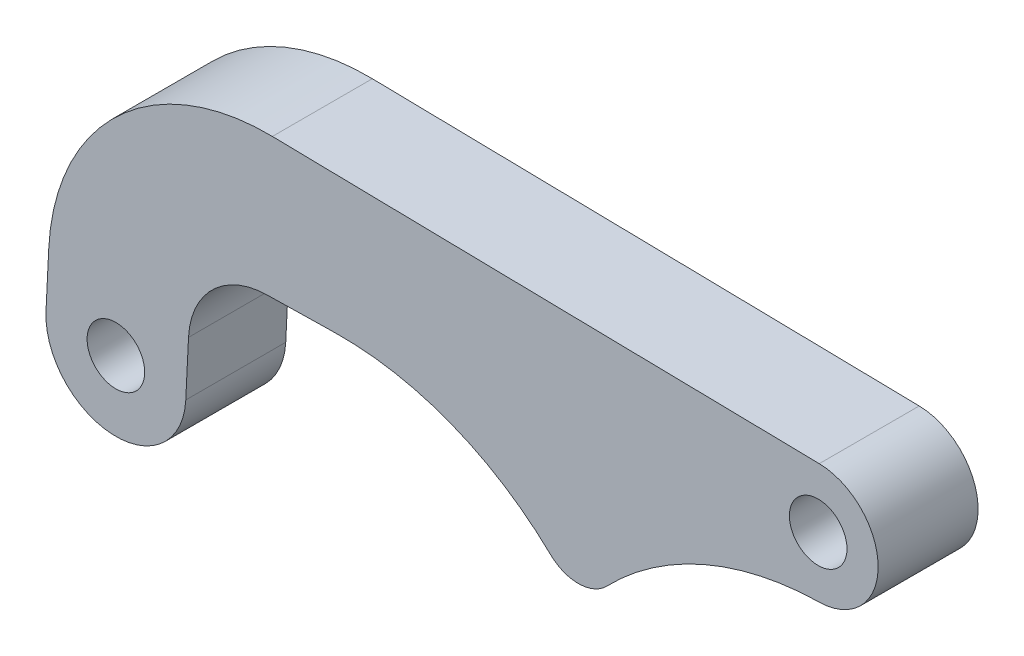
SolidWorks part; units mm, degrees
ref_plane "Front Plane" through (0, 0, 0) normal (0, 0, 1) x (1, 0, 0)
ref_plane "Top Plane" through (0, 0, 0) normal (0, 1, 0) x (1, 0, 0)
ref_plane "Right Plane" through (0, 0, 0) normal (1, 0, 0) x (0, 0, -1)
sketch "Sketch1" plane through (0, 0, 0) normal (0, 0, 1) x (1, 0, 0)
  line L0 (55.8522, 20.4995) -> (12.4263, 21.2892)
  line L5 (0, 0) -> (55.7656, 15.7378) construction
  line L6 (5.5496, -0.2728) -> (5.7665, 4.1413)
  line L7 (-5.5496, 0.2728) -> (-5.3326, 4.6868)
  line L8 (55.7656, 15.7378) -> (12.4263, 15.7378) construction
  line L9 (12.4263, 21.2892) -> (12.4263, 10.1864) construction
  line L10 (17.4058, 10.277) -> (11.9934, 10.1786)
  line L11 (17.4058, 10.277) -> (55.8522, 10.9761) construction
  circle A0 centre (0, 0) radius 2.286
  circle A1 centre (55.7656, 15.7378) radius 2.286
  arc A2 (55.8522, 10.9761) -> (55.8522, 20.4995) centre (55.7656, 15.7378) ccw
  arc A4 (-5.5496, 0.2728) -> (5.5496, -0.2728) centre (0, 0) ccw
  arc A5 (11.9934, 10.1786) -> (5.7665, 4.1413) centre (12.1088, 3.8296) ccw
  arc A6 (12.4263, 21.2892) -> (-5.3326, 4.6868) centre (12.1088, 3.8296) ccw
  arc A7 (12.2226, 3.4494) -> (12.1088, 3.8296) centre (0, 0) ccw construction
  arc A8 (17.4058, 10.277) -> (34.517, 3.5742) centre (17.8436, -13.798) cw
  arc A9 (34.517, 3.5742) -> (38.9959, 3.6556) centre (36.7156, 5.8648) ccw
  arc A10 (38.9959, 3.6556) -> (55.8522, 10.9761) centre (56.29, -13.0989) cw
  point P9 (12.2226, 3.4494)
  point P22 (12.4263, 15.7378)
other "Pen Sketch1" parameters "D1"=16.3026, "D4"=5.6114, "D5"=4.767, "D6"=3.6226, "D7"=4.2424, "D8"=17.8584, "D10"=2.1285, "D2"=28.8294, "D3"=8.5598, "D9"=5.4705, "D11"=16.4867
extrude "Boss-Extrude1" add sketch "Sketch1" along normal mid plane 7.9375
